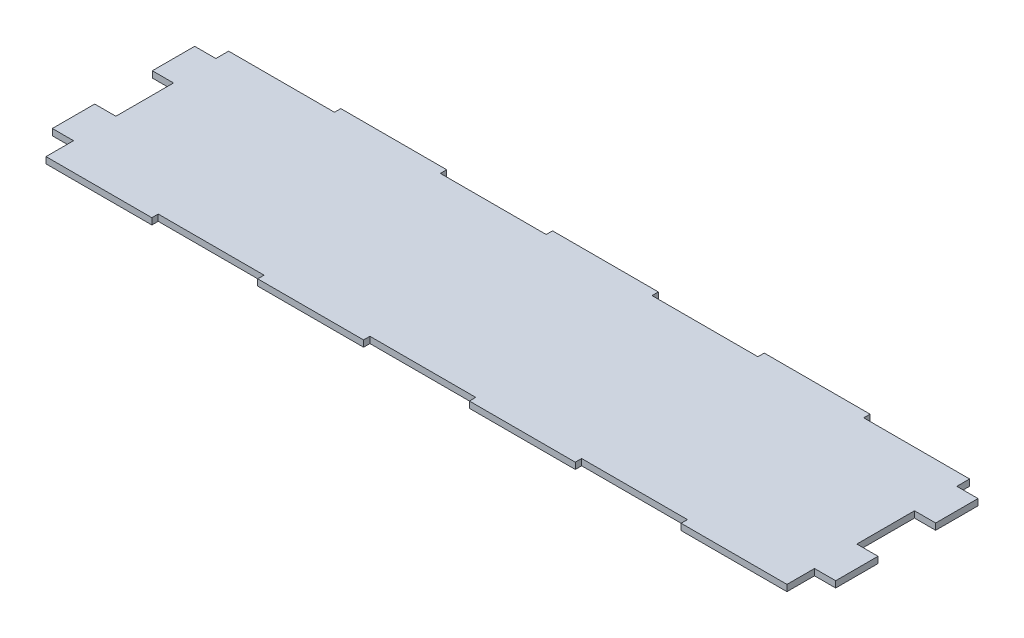
SolidWorks part; units mm, degrees
material "아크릴(내충격성)"
ref_plane "정면" through (0, 0, 0) normal (0, 0, 1) x (1, 0, 0)
ref_plane "윗면" through (0, 0, 0) normal (0, 1, 0) x (1, 0, 0)
ref_plane "우측면" through (0, 0, 0) normal (1, 0, 0) x (0, 0, -1)
sketch "스케치1" plane through (0, 0, 0) normal (0, 1, 0) x (1, 0, 0)
  line L0 (0, 160.8) -> (0, -154.2) construction
  line L2 (-175, 87.23) -> (0, 87.23) construction
  line L5 (-175, 3.97) -> (0, 3.97) construction
  line L7 (-175, 3.97) -> (-175, 13.97)
  line L8 (-175, 13.97) -> (-185, 13.97)
  line L9 (-185, 13.97) -> (-185, 33.97)
  line L10 (-185, 33.97) -> (-175, 33.97)
  line L11 (-175, 33.97) -> (-175, 61.2)
  line L40 (-175, 0.97) -> (0, 0.97) construction
  line L47 (-175, 3.97) -> (-175, 0.97)
  line L48 (-175, 0.97) -> (-125, 0.97)
  line L49 (-125, 0.97) -> (-125, 3.97)
  line L50 (-125, 3.97) -> (-75, 3.97)
  line L51 (-75, 3.97) -> (-75, 0.97)
  line L52 (-75, 0.97) -> (-25, 0.97)
  line L53 (-25, 0.97) -> (-25, 3.97)
  line L54 (-25, 3.97) -> (25, 3.97)
  line L56 (-175, 47.585) -> (-175, 0.97) construction
  line L63 (-185, 61.2) -> (-175, 61.2)
  line L64 (-185, 81.2) -> (-185, 61.2)
  line L65 (-175, 81.2) -> (-185, 81.2)
  line L66 (-175, 87.23) -> (-175, 81.2)
  line L67 (-175, 87.23) -> (-125, 87.23)
  line L91 (-125, 87.23) -> (-125, 90.23)
  line L92 (-125, 90.23) -> (-75, 90.23)
  line L93 (-75, 90.23) -> (-75, 87.23)
  line L94 (-75, 87.23) -> (-25, 87.23)
  line L95 (-25, 87.23) -> (-25, 90.23)
  line L96 (-25, 90.23) -> (25, 90.23)
  line L97 (175, 47.585) -> (175, 0.97) construction
  line L98 (25, 87.23) -> (25, 90.23)
  line L99 (75, 87.23) -> (25, 87.23)
  line L100 (75, 90.23) -> (75, 87.23)
  line L101 (125, 90.23) -> (75, 90.23)
  line L102 (125, 87.23) -> (125, 90.23)
  line L103 (175, 87.23) -> (125, 87.23)
  line L104 (175, 87.23) -> (175, 81.2)
  line L105 (175, 81.2) -> (185, 81.2)
  line L106 (185, 81.2) -> (185, 61.2)
  line L107 (185, 61.2) -> (175, 61.2)
  line L108 (25, 0.97) -> (25, 3.97)
  line L109 (75, 0.97) -> (25, 0.97)
  line L110 (75, 3.97) -> (75, 0.97)
  line L111 (125, 3.97) -> (75, 3.97)
  line L112 (125, 0.97) -> (125, 3.97)
  line L113 (175, 0.97) -> (125, 0.97)
  line L114 (175, 3.97) -> (175, 0.97)
  line L115 (175, 33.97) -> (175, 61.2)
  line L116 (185, 33.97) -> (175, 33.97)
  line L117 (185, 13.97) -> (185, 33.97)
  line L118 (175, 13.97) -> (185, 13.97)
  line L119 (175, 3.97) -> (175, 13.97)
  point P6 (0, 90.23)
  point P22 (0, 3.97)
  point P23 (0, 91.2)
  point P31 (0, 0.97)
  point P36 (0, 0.97)
  point P37 (0, 90.23)
  point P38 (0, 91.2)
  point P40 (0, 94.2)
  dimension "D1" = 6.03
  dimension "D2" = 175
  dimension "D3" = 50
  dimension "D4" = 25
  dimension "D5" = 50
  dimension "D6" = 20
extrude "보스-돌출1" add sketch "스케치1" along normal blind 3
